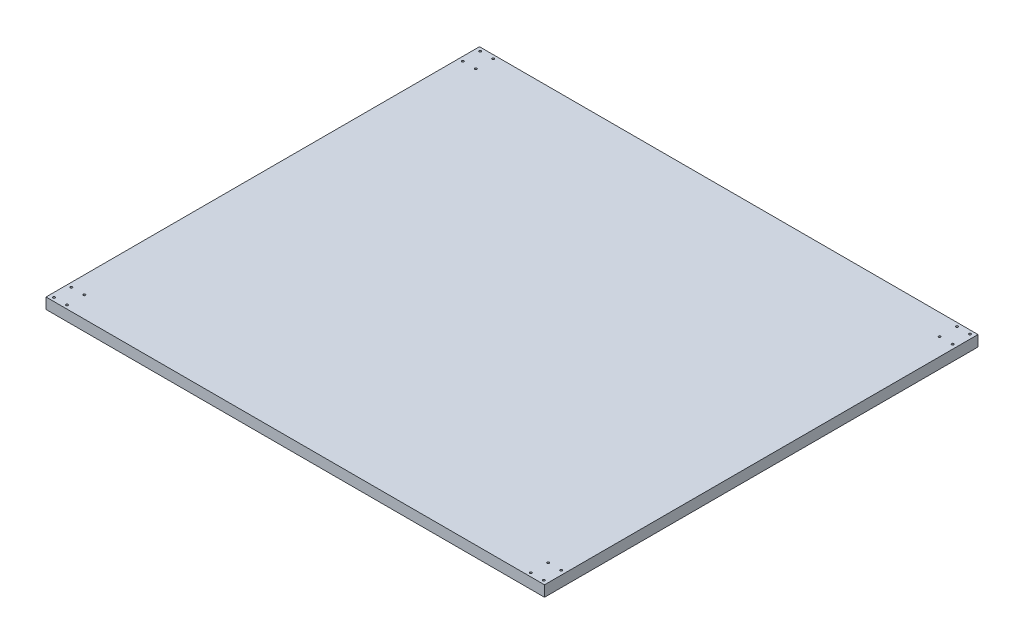
SolidWorks part; units mm, degrees
ref_plane "Alzado" through (0, 0, 0) normal (0, 0, 1) x (1, 0, 0)
ref_plane "Planta" through (0, 0, 0) normal (0, 1, 0) x (1, 0, 0)
ref_plane "Vista lateral" through (0, 0, 0) normal (1, 0, 0) x (0, 0, -1)
sketch "Croquis1" plane through (0, 0, 0) normal (0, 1, 0) x (1, 0, 0)
  line L0 (0, 300) -> (0, -300) construction
  line L1 (-345, -300) -> (345, -300)
  line L2 (-345, -300) -> (-345, 300)
  line L3 (-345, 300) -> (345, 300)
  line L4 (345, -300) -> (345, 300)
  line L5 (-345, -300) -> (345, 300) construction
  line L6 (-345, 300) -> (345, -300) construction
  line L7 (-345, 0) -> (345, 0) construction
  point P0 (0, 0)
  point P10 (0, 0)
  dimension "D1" = 690
  dimension "D2" = 600
extrude "Saliente-Extruir1" add sketch "Croquis1" along normal blind 15
sketch "Croquis2" plane through (0, 15, 0) normal (0, 1, 0) x (1, 0, 0)
  line L0 (0, 300) -> (0, -300) construction
  line L1 (345, 300) -> (-345, 300) construction
  line L2 (-345, -300) -> (345, -300) construction
  line L3 (-345, 0) -> (345, 0) construction
  line L4 (-345, 300) -> (-345, -300) construction
  line L5 (345, -300) -> (345, 300) construction
  line L6 (-187.5, 300) -> (-187.5, -300) construction
  line L7 (187.5, 300) -> (187.5, -300) construction
  line L8 (-345, 187.5) -> (345, 187.5) construction
  line L9 (-345, -187.5) -> (345, -187.5) construction
  dimension "D1" = 187.5
  dimension "D2" = 187.5
  dimension "D3" = 187.5
  dimension "D4" = 187.5
sketch "Croquis3" plane through (0, 15, 0) normal (0, 1, 0) x (1, 0, 0)
  line L0 (345, -300) -> (345, 300) construction
  line L1 (-345, -300) -> (345, -300) construction
  line L2 (0, 300) -> (0, -300) construction
  line L3 (-345, 0) -> (345, 0) construction
  circle A0 centre (339, -295) radius 1.5
  circle A1 centre (321, -295) radius 1.5
  circle A2 centre (321, -271) radius 1.5
  circle A3 centre (339, -271) radius 1.5
  circle A4 centre (-321, -295) radius 1.5
  circle A5 centre (-339, -295) radius 1.5
  circle A6 centre (-339, -271) radius 1.5
  circle A7 centre (-321, -271) radius 1.5
  circle A8 centre (-321, 295) radius 1.5
  circle A9 centre (-339, 295) radius 1.5
  circle A10 centre (-339, 271) radius 1.5
  circle A11 centre (-321, 271) radius 1.5
  circle A12 centre (321, 295) radius 1.5
  circle A13 centre (339, 295) radius 1.5
  circle A14 centre (339, 271) radius 1.5
  circle A15 centre (321, 271) radius 1.5
  dimension "D1" = 3
  dimension "D2" = 18
  dimension "D3" = 6
  dimension "D4" = 24
  dimension "D5" = 5
extrude "Cortar-Extruir1" cut sketch "Croquis3" against normal through all
